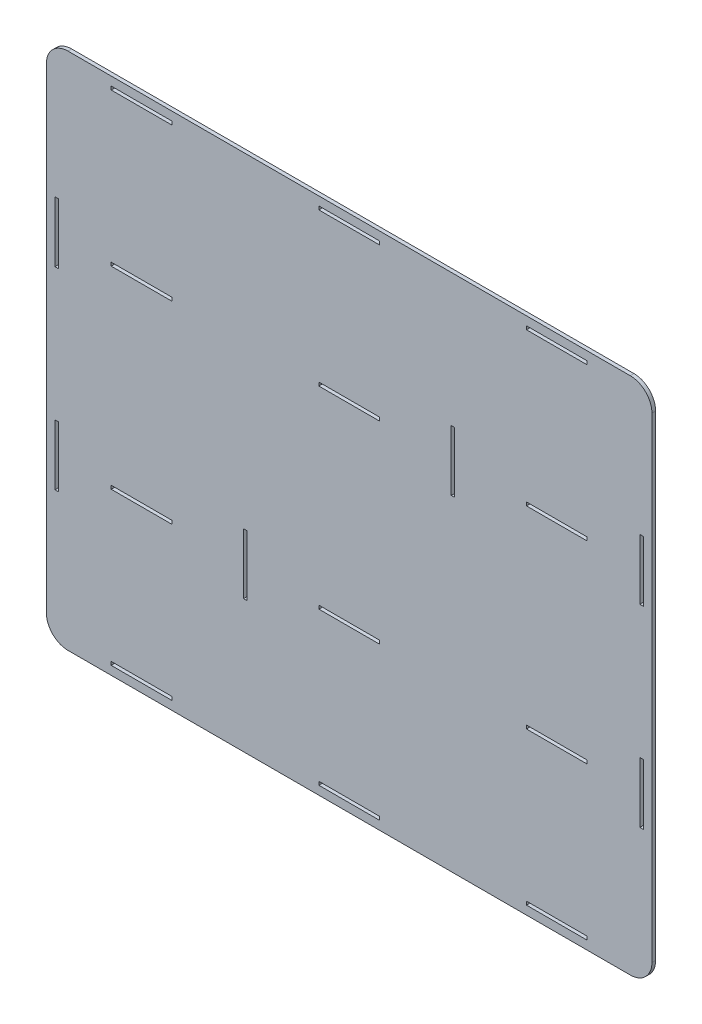
SolidWorks part; units mm, degrees
ref_plane "Front Plane" through (0, 0, 0) normal (0, 0, 1) x (1, 0, 0)
ref_plane "Top Plane" through (0, 0, 0) normal (0, 1, 0) x (1, 0, 0)
ref_plane "Right Plane" through (0, 0, 0) normal (1, 0, 0) x (0, 0, -1)
sketch "Sketch1" plane through (0, 0, 0) normal (0, 0, 1) x (1, 0, 0)
  line L0 (-85, 270) -> (-85, 120) construction
  line L1 (-325, -300) -> (325, -300)
  line L2 (-350, -275) -> (-350, 275)
  line L3 (-325, 300) -> (325, 300)
  line L4 (350, -275) -> (350, 275)
  line L5 (-350, -300) -> (350, 300) construction
  line L6 (-350, 300) -> (350, -300) construction
  line L7 (-85, 120) -> (85, 120) construction
  line L8 (85, 120) -> (85, 270) construction
  line L9 (320, -150) -> (230, -150) construction
  line L10 (230, -150) -> (230, -250) construction
  line L11 (230, -250) -> (320, -250) construction
  line L12 (-320, -152) -> (-186, -152) construction
  line L13 (-186, -152) -> (-186, -248) construction
  line L14 (-186, -248) -> (-320, -248) construction
  line L15 (0, 300) -> (0, -300) construction
  line L16 (-350, 0) -> (350, 0) construction
  line L17 (-275, -286) -> (-275, -290)
  line L18 (340, -76.6666) -> (336, -76.6666)
  line L19 (340, -76.6666) -> (340, -146.6666)
  line L20 (340, -146.6666) -> (336, -146.6666)
  line L21 (336, -76.6666) -> (336, -146.6666)
  line L22 (336, 146.6667) -> (340, 146.6667)
  line L23 (336, 146.6667) -> (336, 76.6667)
  line L24 (336, 76.6667) -> (340, 76.6667)
  line L25 (340, 146.6667) -> (340, 76.6667)
  line L30 (-35, -286) -> (35, -286)
  line L31 (-35, -286) -> (-35, -290)
  line L32 (-35, -290) -> (35, -290)
  line L33 (35, -286) -> (35, -290)
  line L34 (205, -286) -> (275, -286)
  line L35 (205, -286) -> (205, -290)
  line L36 (205, -290) -> (275, -290)
  line L37 (275, -286) -> (275, -290)
  line L38 (-205, -290) -> (-275, -290)
  line L39 (-205, -286) -> (-205, -290)
  line L40 (-205, -286) -> (-275, -286)
  line L45 (-340, 146.6667) -> (-340, 76.6667)
  line L46 (-336, 76.6667) -> (-340, 76.6667)
  line L47 (-336, 146.6667) -> (-336, 76.6667)
  line L48 (-336, 146.6667) -> (-340, 146.6667)
  line L49 (-336, -76.6666) -> (-336, -146.6666)
  line L50 (-340, -146.6666) -> (-336, -146.6666)
  line L51 (-340, -76.6666) -> (-340, -146.6666)
  line L52 (-340, -76.6666) -> (-336, -76.6666)
  line L61 (320, -250) -> (320, -150) construction
  line L62 (-320, -152) -> (-320, -248) construction
  line L63 (-85, 270) -> (85, 270) construction
  line L64 (-340, 290) -> (340, 290) construction
  line L65 (340, -290) -> (340, 290) construction
  line L66 (-340, -290) -> (340, -290) construction
  line L67 (-340, -290) -> (-340, 290) construction
  line L72 (122, 146.6667) -> (118, 146.6667)
  line L73 (122, 146.6667) -> (122, 76.6667)
  line L74 (122, 76.6667) -> (118, 76.6667)
  line L75 (118, 146.6667) -> (118, 76.6667)
  line L80 (-330, 280) -> (330, 280) construction
  line L81 (330, -280) -> (330, 280) construction
  line L82 (-330, -280) -> (330, -280) construction
  line L83 (-330, -280) -> (-330, 280) construction
  line L84 (-118, -146.6667) -> (-118, -76.6667)
  line L85 (-118, -76.6667) -> (-122, -76.6667)
  line L86 (-122, -146.6667) -> (-122, -76.6667)
  line L87 (-118, -146.6667) -> (-122, -146.6667)
  line L92 (-35, 113.6667) -> (35, 113.6667)
  line L93 (-35, 113.6667) -> (-35, 109.6667)
  line L94 (-35, 109.6667) -> (35, 109.6667)
  line L95 (35, 113.6667) -> (35, 109.6667)
  line L96 (-275, 113.6667) -> (-205, 113.6667)
  line L97 (-275, 113.6667) -> (-275, 109.6667)
  line L98 (-275, 109.6667) -> (-205, 109.6667)
  line L99 (-205, 113.6667) -> (-205, 109.6667)
  line L100 (205, 113.6667) -> (275, 113.6667)
  line L101 (205, 113.6667) -> (205, 109.6667)
  line L102 (205, 109.6667) -> (275, 109.6667)
  line L103 (275, 113.6667) -> (275, 109.6667)
  line L104 (-275, -113.6667) -> (-275, -109.6667)
  line L105 (-275, -109.6667) -> (-205, -109.6667)
  line L106 (-205, -113.6667) -> (-205, -109.6667)
  line L107 (-275, -113.6667) -> (-205, -113.6667)
  line L108 (-35, -113.6667) -> (-35, -109.6667)
  line L109 (-35, -109.6667) -> (35, -109.6667)
  line L110 (35, -113.6667) -> (35, -109.6667)
  line L111 (-35, -113.6667) -> (35, -113.6667)
  line L112 (205, -113.6667) -> (205, -109.6667)
  line L113 (205, -109.6667) -> (275, -109.6667)
  line L114 (275, -113.6667) -> (275, -109.6667)
  line L115 (205, -113.6667) -> (275, -113.6667)
  line L116 (-205, 286) -> (-275, 286)
  line L117 (-205, 286) -> (-205, 290)
  line L118 (-205, 290) -> (-275, 290)
  line L119 (-275, 286) -> (-275, 290)
  line L120 (-35, 290) -> (35, 290)
  line L121 (35, 286) -> (35, 290)
  line L122 (-35, 286) -> (35, 286)
  line L123 (-35, 286) -> (-35, 290)
  line L124 (205, 290) -> (275, 290)
  line L125 (275, 286) -> (275, 290)
  line L126 (205, 286) -> (275, 286)
  line L127 (205, 286) -> (205, 290)
  line L128 (-338, -288) -> (-338, 288) construction
  line L129 (-338, 288) -> (338, 288) construction
  line L130 (338, -288) -> (338, 288) construction
  line L131 (-338, -288) -> (338, -288) construction
  line L132 (-350, -300) -> (350, -300) construction
  line L133 (-350, -300) -> (-350, 300) construction
  line L134 (350, -300) -> (350, 300) construction
  line L135 (-350, 300) -> (350, 300) construction
  arc A0 (-325, -300) -> (-350, -275) centre (-325, -275) cw
  arc A1 (325, -300) -> (350, -275) centre (325, -275) ccw
  arc A2 (350, 275) -> (325, 300) centre (325, 275) ccw
  arc A3 (-350, 275) -> (-325, 300) centre (-325, 275) cw
  point P0 (0, 0)
  point P8 (0, 300)
  point P11 (0, 120)
  point P18 (230, -171.7)
  point P22 (-186, -220.5)
  point P24 (-186, -200)
  point P25 (230, -200)
  point P53 (35, -288)
  point P55 (275, -200)
  point P56 (-253, -200)
  point P57 (0, -286)
  point P73 (320, -200)
  point P74 (0, 195)
  point P75 (338, -76.6666)
  point P77 (-275, 111.6667)
  point P78 (-336, 111.6667)
  point P85 (120, 146.6667)
  point P86 (340, 111.6667)
  point P89 (275, -150)
  point P90 (-253, -152)
  point P91 (340, -111.6666)
  point P92 (-320, -200)
  point P93 (85, 195)
  point P98 (-205, -111.6667)
  point P100 (35, 111.6667)
  point P101 (118, 111.6667)
  point P102 (240, -290)
  point P103 (-122, -111.6667)
  point P109 (240, 113.6667)
  point P115 (0, 113.6667)
  point P116 (-120, -146.6667)
  point P157 (240, 109.6667)
  dimension "D29" = 25
  dimension "D1" = 600
  dimension "D2" = 700
  dimension "D3" = 170
  dimension "D4" = 150
  dimension "D5" = 100
  dimension "D6" = 90
  dimension "D7" = 134
  dimension "D8" = 96
  dimension "D9" = 21.7
  dimension "D10" = 27.5
  dimension "D11" = 50
  dimension "D12" = 70
  dimension "D13" = 576
  dimension "D14" = 12
  dimension "D15" = 153.3333
  dimension "D16" = 70
  dimension "D17" = 4
  dimension "D18" = 153.3333
  dimension "D19" = 2
  dimension "D20" = 676
  dimension "D21" = 176.3333
  dimension "D22" = 223.3333
  dimension "D23" = 12
  dimension "D24" = 70
  dimension "D25" = 4
  dimension "D26" = 70
  dimension "D27" = 98
  dimension "D28" = 153.3334
  dimension "D30" = 120
  dimension "D31" = 230
  dimension "D32" = 30
  dimension "D33" = 75
  dimension "D34" = 30
  dimension "D35" = 97
  dimension "D36" = 30
  dimension "D37" = 105
  dimension "D39" = 580
  dimension "D40" = 680
  dimension "D43" = 70
  dimension "D44" = 4
  dimension "D45" = 70
  dimension "D46" = 4
  dimension "D47" = 20
  dimension "D48" = 660
  dimension "D49" = 560
  dimension "D54" = 70
  dimension "D55" = 4
  dimension "D56" = 70
  dimension "D57" = 4
  dimension "D59" = 100
  dimension "D38" = 10
extrude "Boss-Extrude1" add sketch "Sketch1" along normal blind 4.3
